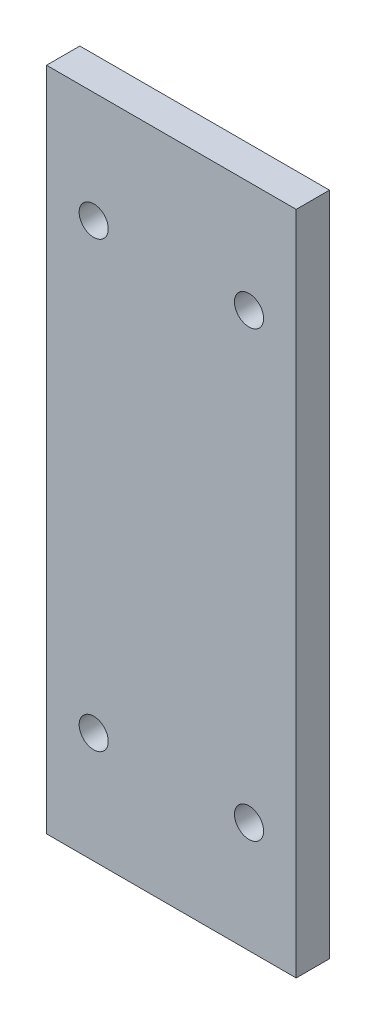
SolidWorks part; units mm, degrees
material "1.0037 (S235JR)"
ref_plane "Płaszczyzna przednia" through (0, 0, 0) normal (0, 0, 1) x (1, 0, 0)
ref_plane "Płaszczyzna górna" through (0, 0, 0) normal (0, 1, 0) x (1, 0, 0)
ref_plane "Płaszczyzna prawa" through (0, 0, 0) normal (1, 0, 0) x (0, 0, -1)
sketch "Szkic1" plane through (0, 0, 0) normal (0, 0, 1) x (1, 0, 0)
  line L0 (-40, -40) -> (-40, -720) construction
  line L1 (5, -720) -> (-85, -720)
  line L2 (5, -720) -> (5, -480)
  line L3 (5, -480) -> (-85, -480)
  line L4 (-85, -720) -> (-85, -480)
  line L5 (-72, -72) -> (-8, -8) construction
  dimension "D1" = 90
  dimension "D2" = 240
  dimension "D3" = 0
extrude "Dodanie-wyciągnięcie1" add sketch "Szkic1" along normal blind 12
sketch "Szkic2" plane through (0, 0, 0) normal (0, 0, -1) x (-1, 0, 0)
  line L0 (40, -720) -> (40, -480) construction
  line L1 (85, -720) -> (-5, -720) construction
  line L2 (-5, -480) -> (85, -480) construction
  line L3 (-5, -600) -> (85, -600) construction
  line L4 (-5, -720) -> (-5, -480) construction
  line L5 (85, -480) -> (85, -720) construction
sketch "Szkic3" plane through (0, 0, 12) normal (0, 0, 1) x (1, 0, 0)
  line L0 (-85, -600) -> (5, -600) construction
  line L1 (-85, -480) -> (-85, -720) construction
  line L2 (5, -720) -> (5, -480) construction
  line L3 (-40, -480) -> (-40, -600) construction
  line L4 (5, -480) -> (-85, -480) construction
  point P6 (-68, -520)
  point P7 (-12, -520)
  point P12 (-68, -680)
  point P13 (-12, -680)
  dimension "D1" = 56
  dimension "D2" = 28
  dimension "D3" = 80
hole_wizard "Otwór gwintowany M12x1.51" positions "Szkic5" profile "Szkic4" tap size "M12x1.5" standard "Ansi Metric" end condition through all
sketch "Szkic5" plane through (0, 0, 12) normal (0, 0, 1) x (1, 0, 0)
  point P0 (-68, -520)
  point P2 (-68, -680)
  point P4 (-12, -680)
  point P6 (-12, -520)
sketch "Szkic4" plane through (-68, -520, 12) normal (1, 0, 0) x (0, -1, 0)
  line L0 (0, 0) -> (0, 12)
  line L1 (0, 12) -> (5.25, 12)
  line L2 (5.25, 12) -> (5.25, 0)
  line L5 (5.25, 0) -> (0, 0)
  line L11 (0, -6.35) -> (0, 107.95) construction
  dimension "Średnica zewnętrzna gwintu" = 10.5
  dimension "Głębokość otworu gwintowanego na wylot" = 12
